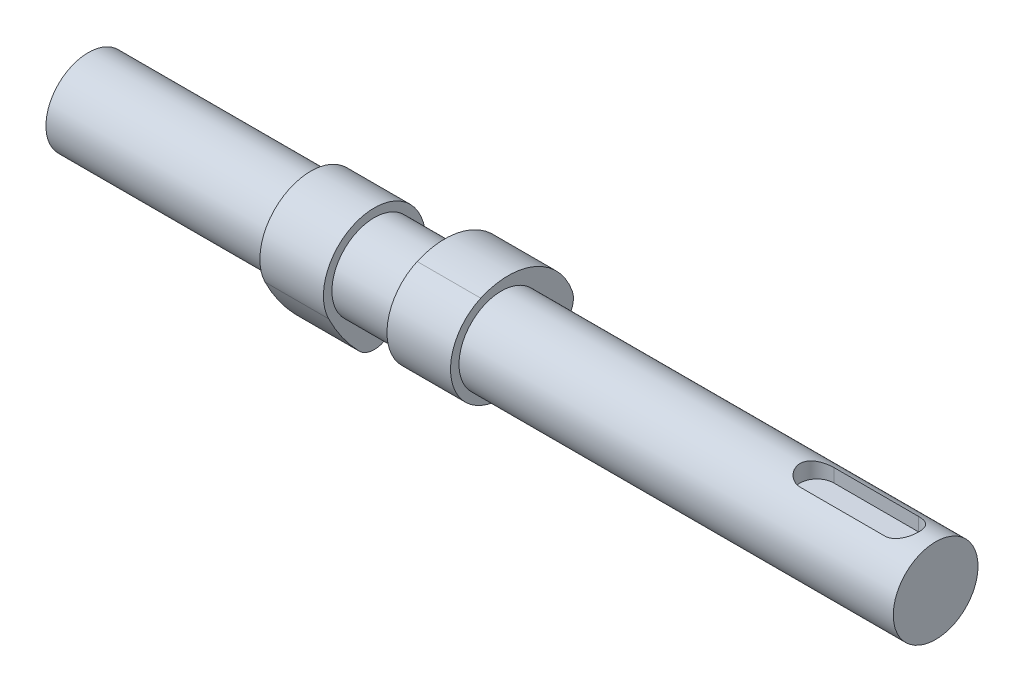
SolidWorks part; units mm, degrees
ref_plane "Front Plane" through (0, 0, 0) normal (0, 0, 1) x (1, 0, 0)
ref_plane "Top Plane" through (0, 0, 0) normal (0, 1, 0) x (1, 0, 0)
ref_plane "Right Plane" through (0, 0, 0) normal (1, 0, 0) x (0, 0, -1)
sketch "Sketch1" plane through (0, 0, 0) normal (1, 0, 0) x (0, 0, -1)
  circle A0 centre (0, 0) radius 10
  dimension "D1" = 20
extrude "Boss-Extrude1" add sketch "Sketch1" against normal blind 75 and the other way blind 125
sketch "Sketch2" plane through (0, 0, 0) normal (1, 0, 0) x (0, 0, -1)
  line L0 (7, 0) -> (11.997, 0) construction
  arc A0 (-4.8671, 10.9687) -> (5.3062, -10.7631) centre (0, 0) ccw
  arc A1 (15.4795, -3.5877) -> (16.7127, 1.6619) centre (11.997, 0) ccw
  arc A2 (-4.8671, 10.9687) -> (16.7127, 1.6619) centre (1.6224, -3.6562) cw
  arc A3 (5.3062, -10.7631) -> (15.4795, -3.5877) centre (-12.3812, 25.1139) ccw
  dimension "D1" = 24
  dimension "D2" = 10
  dimension "D3" = 16
  dimension "D4" = 40
  dimension "D5" = 12.5
extrude "Boss-Extrude2" add sketch "Sketch2" along normal mid plane 15 from offset 15 separate body
mirror "Mirror5" about plane through (0, 0, 0) normal (1, 0, 0) of bodies 102
move or copy body "Body-Move/Copy1" bodies to move or copy 103 copy no rotation origin (0, 0, 0) rotation axis (-1, 0, 0) rotation angle 90
ref_plane "Plane1" through (0, 10, 0) normal (0, 1, 0) x (1, 0, 0)
sketch "Sketch3" plane through (0, 10, 0) normal (0, 1, 0) x (1, 0, 0)
  line L0 (125, 0) -> (95.4029, 0) construction
  line L1 (125, -10) -> (125, 10) construction
  line L2 (97, 0) -> (117, 0) construction
  line L3 (97, 4) -> (117, 4)
  line L4 (97, -4) -> (117, -4)
  arc A0 (97, 4) -> (97, -4) centre (97, 0) ccw
  arc A1 (117, -4) -> (117, 4) centre (117, 0) ccw
  point P7 (107, 0)
  dimension "D3" = 4
  dimension "D1" = 20
  dimension "D2" = 8
extrude "Cut-Extrude1" cut sketch "Sketch3" against normal blind 4
